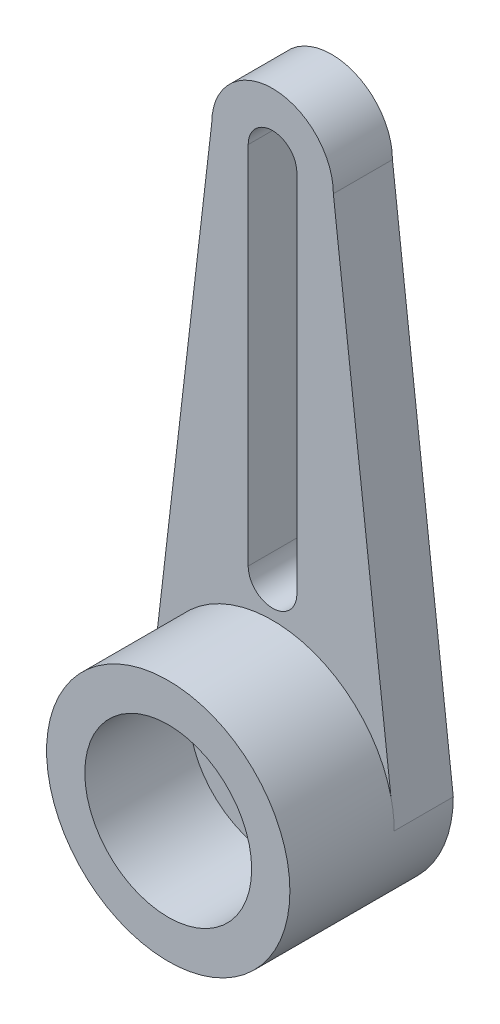
SolidWorks part; units mm, degrees
ref_plane "Alzado" through (0, 0, 0) normal (0, 0, 1) x (1, 0, 0)
ref_plane "Planta" through (0, 0, 0) normal (0, 1, 0) x (1, 0, 0)
ref_plane "Vista lateral" through (0, 0, 0) normal (1, 0, 0) x (0, 0, -1)
sketch "Croquis1" plane through (0, 0, 0) normal (0, 0, 1) x (1, 0, 0)
  line L0 (0, 0) -> (0, 15) construction
  line L1 (-1.75, 15) -> (-3.5, 0)
  line L2 (1.75, 15) -> (3.5, 0)
  line L3 (0.7, 15) -> (0.7, 4.5)
  line L4 (-0.7, 4.5) -> (-0.7, 15)
  arc A0 (-3.406, 0.8057) -> (3.406, 0.8057) centre (0, 0) ccw
  arc A1 (1.75, 15) -> (-1.75, 15) centre (0, 15) ccw
  circle A2 centre (0, 0) radius 1.1
  arc A3 (0.7, 15) -> (-0.7, 15) centre (0, 15) ccw
  arc A4 (-0.7, 4.5) -> (0.7, 4.5) centre (0, 4.5) ccw
  dimension "D1" = 7
  dimension "D2" = 3.5
  dimension "D4" = 2.2
  dimension "D5" = 0.7
  dimension "D6" = 0.7
  dimension "D3" = 15
  dimension "D7" = 10.5
extrude "Saliente-Extruir1" add sketch "Croquis1" along normal blind 1.7
sketch "Croquis2" plane through (0, 0, 1.7) normal (0, 0, 1) x (1, 0, 0)
  circle A0 centre (0, 0) radius 3.5
  circle A1 centre (0, 0) radius 2.4
  dimension "D1" = 1.1
  dimension "D2" = 7
extrude "Saliente-Extruir2" add sketch "Croquis2" along normal blind 3
sketch "Croquis3" plane through (0, 0, 0) normal (0, 0, -1) x (-1, 0, 0)
  circle A0 centre (0, 0) radius 2.25
  dimension "D1" = 4.5
extrude "Cortar-Extruir1" cut sketch "Croquis3" against normal blind 1
